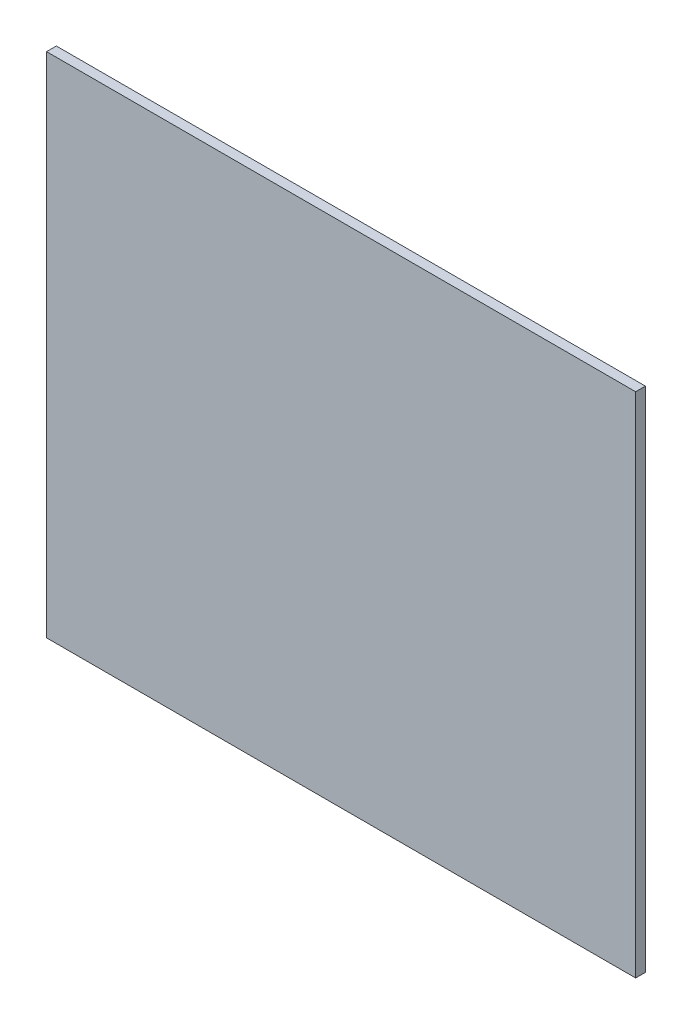
SolidWorks part; units mm, degrees
ref_plane "Front Plane" through (0, 0, 0) normal (0, 0, 1) x (1, 0, 0)
ref_plane "Top Plane" through (0, 0, 0) normal (0, 1, 0) x (1, 0, 0)
ref_plane "Right Plane" through (0, 0, 0) normal (1, 0, 0) x (0, 0, -1)
sketch "Sketch1" plane through (0, 0, 10) normal (0, 0, 1) x (1, 0, 0)
  line L4 (-10, 140) -> (-10, -10)
  line L5 (-10, -10) -> (165, -10)
  line L6 (165, -10) -> (165, 140)
  line L7 (165, 140) -> (-10, 140)
  line L8 (-10, 140) -> (-10, -10) construction
  line L9 (-10, -10) -> (165, -10) construction
  line L10 (165, -10) -> (165, 140) construction
  line L11 (165, 140) -> (-10, 140) construction
  line L16 (-13, 143) -> (-13, -13)
  line L17 (-13, -13) -> (168, -13)
  line L18 (168, -13) -> (168, 143)
  line L19 (168, 143) -> (-13, 143)
  line L20 (-13, 143) -> (-13, -13)
  line L21 (-13, -13) -> (168, -13)
  line L22 (168, -13) -> (168, 143)
  line L23 (168, 143) -> (-13, 143)
  dimension "D1" = 0
  dimension "D2" = 3
extrude "Boss-Extrude1" add sketch "Sketch1" along normal blind 3
